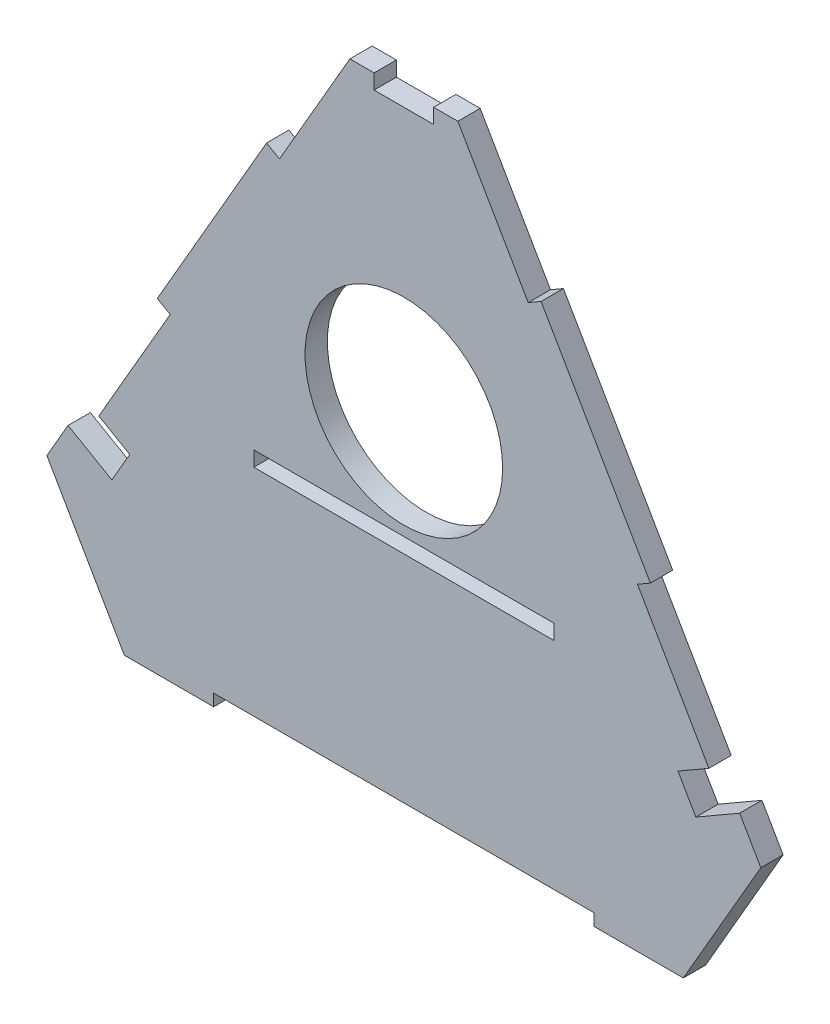
SolidWorks part; units mm, degrees
material "Teak"
ref_plane "Front Plane" through (0, 0, 0) normal (0, 0, 1) x (1, 0, 0)
ref_plane "Top Plane" through (0, 0, 0) normal (0, 1, 0) x (1, 0, 0)
ref_plane "Right Plane" through (0, 0, 0) normal (1, 0, 0) x (0, 0, -1)
sketch "Sketch3" plane through (0, 0, 0) normal (0, 0, 1) x (1, 0, 0)
  line L0 (0, 0) -> (0, 24.9323) construction
  line L1 (63.5, 505.932) -> (-63.5, 505.932)
  line L2 (-63.5, 505.932) -> (-317.5, 65.9911)
  line L3 (-317.5, 65.9911) -> (-279.4, 0)
  line L4 (-279.4, 0) -> (279.4, 0)
  line L5 (0, 0) -> (113.9484, 0) construction
  line L6 (317.5, 65.9911) -> (279.4, 0)
  line L7 (63.5, 505.932) -> (317.5, 65.9911)
  line L8 (60.7504, 501.1695) -> (312.0007, 65.9911)
  line L9 (312.0007, 65.9911) -> (276.6504, 4.7625)
  line L10 (-276.6504, 4.7625) -> (276.6504, 4.7625)
  line L11 (-312.0007, 65.9911) -> (-276.6504, 4.7625)
  line L12 (-60.7504, 501.1695) -> (-312.0007, 65.9911)
  line L13 (60.7504, 501.1695) -> (-60.7504, 501.1695)
  line L14 (-172.2913, 317.5) -> (172.2913, 317.5)
  point P13 (0, 0)
  point P15 (0, 505.932)
  dimension "D1" = 60
  dimension "D2" = 279.4
  dimension "D3" = 508
  dimension "D4" = 60
  dimension "D5" = 76.2
  dimension "D6" = 4.7625
  dimension "D7" = 317.5
extrude "Boss-Extrude1" add sketch "Sketch3" along normal blind 4.7625 contours L14 L12 L11 L10 L9 L8 | L12 L14 L8 L13
scale "Scale2" scale about centroid uniform scaling no x scale factor 0.25 y scale factor 0.25 z scale factor 1
sketch "Sketch8" plane through (0, 0, 4.7625) normal (0, 0, 1) x (1, 0, 0)
  line L1 (0, 0) -> (0, 346.8045) construction
  line L2 (-69.1626, 150.1171) -> (69.1626, 150.1171) construction
  circle A0 centre (0, 214.8871) radius 21.082
  dimension "D1" = 42.164
  dimension "D2" = 64.77
extrude "Cut-Extrude5" cut sketch "Sketch8" against normal through all
sketch "Sketch9" plane through (0, 0, 4.7625) normal (0, 0, 1) x (1, 0, 0)
  line L1 (-32.0167, 191.7191) -> (32.0167, 191.7191)
  line L2 (-32.0167, 191.7191) -> (-32.0167, 188.5187)
  line L3 (-32.0167, 188.5187) -> (32.0167, 188.5187)
  line L4 (32.0167, 191.7191) -> (32.0167, 188.5187)
  line L5 (-32.0167, 191.7191) -> (32.0167, 188.5187) construction
  line L6 (-32.0167, 188.5187) -> (32.0167, 191.7191) construction
  line L7 (0, 0) -> (0, 422.9525) construction
  line L8 (-69.1626, 150.1171) -> (69.1626, 150.1171) construction
  point P0 (0, 190.1189)
  dimension "D1" = 3.2004
  dimension "D2" = 38.4016
  dimension "D3" = 64.0334
extrude "Cut-Extrude8" cut sketch "Sketch9" against normal through all and the other way through all
sketch "Sketch10" plane through (0, 0, 4.7625) normal (0, 0, 1) x (1, 0, 0)
  line L0 (-6.35, 274.2188) -> (-6.35, 271.0438)
  line L1 (15.1876, 274.2188) -> (-15.1876, 274.2188) construction
  line L2 (-6.35, 271.0438) -> (6.35, 271.0438)
  line L3 (6.35, 271.0438) -> (6.35, 274.2188)
  line L4 (6.35, 274.2188) -> (-6.35, 274.2188)
  line L5 (0, 0) -> (0, 548.4377) construction
  point P9 (0, 274.2188)
  dimension "D1" = 12.7
  dimension "D2" = 3.175
extrude "Cut-Extrude9" cut sketch "Sketch10" against normal through all
sketch "Sketch11" plane through (0, 0, 4.7625) normal (0, 0, 1) x (1, 0, 0)
  line L0 (15.1876, 274.2188) -> (29.2846, 249.8021)
  line L1 (29.2846, 249.8021) -> (26.535, 248.2146)
  line L2 (26.535, 248.2146) -> (11.5214, 274.2188)
  line L3 (11.5214, 274.2188) -> (15.1876, 274.2188)
  line L4 (0, 183.7516) -> (0, 317.8954) construction
  line L9 (15.1876, 274.2188) -> (78.0002, 165.4242) construction
  line L10 (-29.2846, 249.8021) -> (-26.535, 248.2146)
  line L11 (-15.1876, 274.2188) -> (-29.2846, 249.8021)
  line L12 (-11.5214, 274.2188) -> (-15.1876, 274.2188)
  line L13 (-26.535, 248.2146) -> (-11.5214, 274.2188)
  dimension "D1" = 28.194
  dimension "D2" = 3.175
extrude "Cut-Extrude10" cut sketch "Sketch11" against normal through all
sketch "Sketch12" plane through (0, 0, 4.7625) normal (0, 0, 1) x (1, 0, 0)
  line L0 (29.2846, 249.8021) -> (78.0002, 165.4242) construction
  line L1 (71.6502, 176.4228) -> (52.6002, 209.4183)
  line L2 (52.6002, 209.4183) -> (49.8506, 207.8308)
  line L3 (71.6502, 176.4228) -> (68.9006, 174.8353)
  line L4 (68.9006, 174.8353) -> (49.8506, 207.8308)
  line L5 (0, 0) -> (0, 358.9711) construction
  line L6 (-71.6502, 176.4228) -> (-68.9006, 174.8353)
  line L7 (-71.6502, 176.4228) -> (-52.6002, 209.4183)
  line L8 (-52.6002, 209.4183) -> (-49.8506, 207.8308)
  line L9 (-68.9006, 174.8353) -> (-49.8506, 207.8308)
  dimension "D1" = 38.1
  dimension "D2" = 3.175
  dimension "D3" = 12.7
extrude "Cut-Extrude11" cut sketch "Sketch12" against normal through all
sketch "Sketch13" plane through (0, 0, 4.7625) normal (0, 0, 1) x (1, 0, 0)
  line L0 (78.0002, 165.4242) -> (76.1671, 168.5992)
  line L1 (71.6502, 176.4228) -> (78.0002, 165.4242) construction
  line L2 (76.1671, 168.5992) -> (62.5506, 145.0147)
  line L3 (62.5506, 145.0147) -> (65.3002, 143.4272)
  line L4 (78.0002, 165.4242) -> (69.1626, 150.1171) construction
  line L5 (65.3002, 143.4272) -> (78.0002, 165.4242)
  line L6 (0, 0) -> (0, 409.0058) construction
  line L7 (-62.5506, 145.0147) -> (-65.3002, 143.4272)
  line L8 (-76.1671, 168.5992) -> (-62.5506, 145.0147)
  line L9 (-78.0002, 165.4242) -> (-76.1671, 168.5992)
  line L10 (-65.3002, 143.4272) -> (-78.0002, 165.4242)
  dimension "D1" = 25.4
  dimension "D2" = 3.175
extrude "Cut-Extrude12" cut sketch "Sketch13" against normal through all
sketch "Sketch17" plane through (0, 0, 4.7625) normal (0, 0, 1) x (1, 0, 0)
  line L0 (0, 191.7191) -> (0, 193.8646) construction
  line L1 (32.0167, 191.7191) -> (-32.0167, 191.7191) construction
  dimension "D1" = 2.1455
sketch "Sketch18" plane through (0, 0, 0) normal (0, 0, -1) x (-1, 0, 0)
  line L0 (-65.4964, 150.1171) -> (-59.6305, 139.9571)
  line L1 (-59.6305, 139.9571) -> (-40.5805, 139.9571)
  line L2 (-40.5805, 139.9571) -> (-40.5805, 150.1171)
  line L3 (65.4964, 150.1171) -> (-65.4964, 150.1171) construction
  line L4 (-76.1671, 168.5992) -> (-65.4964, 150.1171) construction
  line L5 (-40.5805, 142.4971) -> (40.5805, 142.4971)
  line L6 (0, 142.4971) -> (0, 150.1171)
  line L7 (0, 2.6194) -> (0, -2.6194) construction
  line L8 (40.5805, 139.9571) -> (40.5805, 150.1171)
  line L9 (59.6305, 139.9571) -> (40.5805, 139.9571)
  line L10 (65.4964, 150.1171) -> (59.6305, 139.9571)
  point P11 (0, 150.1171)
  line M13 (-65.4964, 150.1171) -> (65.4964, 150.1171)
  dimension "D1" = 19.05
  dimension "D2" = 10.16
  dimension "D3" = 2.54
extrude "Boss-Extrude2" add sketch "Sketch18" against normal up to surface (4.7625 mm away) contours L1 L2 L0 M13 | L5 L6 L2 M13 | L5 L8 L6 M13 | L10 L8 L9 M13 up to face at (0, 218.6111, 4.7625)
sketch "Sketch19" plane through (0, 0, 0) normal (0, 0, -1) x (-1, 0, 0)
  line L0 (-61.623, 143.408) -> (-56.2925, 139.9571)
  line L1 (-61.623, 143.408) -> (-58.172, 148.7385)
  line L2 (-56.2925, 139.9571) -> (-52.8416, 145.2875)
  line L3 (-58.172, 148.7385) -> (-52.8416, 145.2875)
  line L4 (-76.1671, 168.5992) -> (-59.6305, 139.9571) construction
  line L5 (-59.6305, 139.9571) -> (-40.5805, 139.9571) construction
  dimension "D1" = 6.35
  dimension "D2" = 6.35
sketch "Sketch20" plane through (0, 0, 0) normal (0, 0, -1) x (-1, 0, 0)
  line L0 (68.9006, 174.8353) -> (65.0906, 181.4344)
  line L1 (68.9006, 174.8353) -> (62.3014, 171.0253)
  line L2 (65.0906, 181.4344) -> (58.4914, 177.6244)
  line L3 (62.3014, 171.0253) -> (58.4914, 177.6244)
  line L4 (68.9006, 174.8353) -> (49.8506, 207.8308) construction
  dimension "D1" = 7.62
  dimension "D2" = 7.62
extrude "Cut-Extrude13" cut sketch "Sketch20" against normal up to next
mirror "Mirror1" about plane through (0, 0, 0) normal (1, 0, 0) of "Cut-Extrude13"
